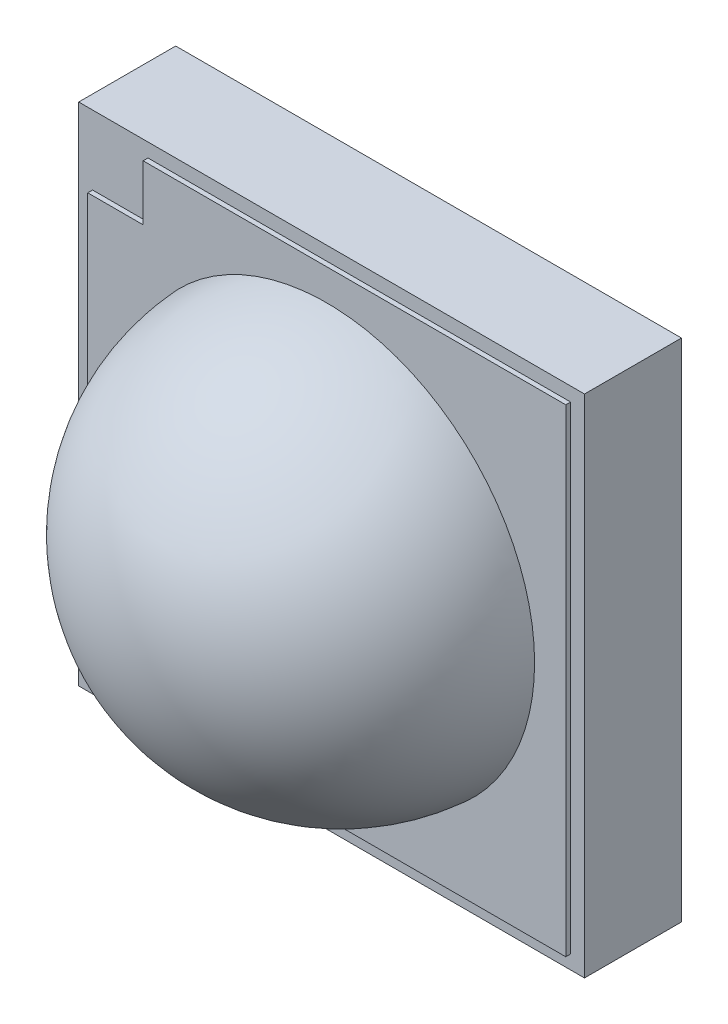
SolidWorks part; units mm, degrees
ref_plane "Front" through (0, 0, 0) normal (0, 0, 1) x (1, 0, 0)
ref_plane "Top" through (0, 0, 0) normal (0, 1, 0) x (1, 0, 0)
ref_plane "Right" through (0, 0, 0) normal (1, 0, 0) x (0, 0, -1)
sketch "Эскиз1" plane through (0, 0, 0) normal (0, 0, 1) x (1, 0, 0)
  line L1 (0.725, -1.625) -> (-0.525, -1.625)
  line L2 (0.725, -1.625) -> (0.725, 1.625)
  line L3 (0.725, 1.625) -> (-0.725, 1.625)
  line L4 (-0.725, -1.425) -> (-0.725, 1.625)
  line L5 (0.725, -1.625) -> (-0.725, 1.625) construction
  line L6 (0.725, 1.625) -> (-0.725, -1.625) construction
  line L7 (1.635, -1.625) -> (1.105, -1.625)
  line L8 (-1.105, -1.625) -> (-1.635, -1.625)
  line L9 (-1.105, -1.625) -> (-1.105, -0.875)
  line L10 (-1.105, -0.875) -> (-1.635, -0.875)
  line L11 (-1.635, -1.625) -> (-1.635, -0.875)
  line L12 (-1.105, -1.625) -> (-1.635, -0.875) construction
  line L13 (-1.105, -0.875) -> (-1.635, -1.625) construction
  line L14 (1.635, -1.625) -> (1.635, -0.875)
  line L15 (1.635, -0.875) -> (1.105, -0.875)
  line L16 (1.105, -1.625) -> (1.105, -0.875)
  line L17 (1.635, -0.375) -> (1.105, -0.375)
  line L18 (1.635, -0.375) -> (1.635, 0.375)
  line L19 (1.635, 0.375) -> (1.105, 0.375)
  line L20 (1.105, -0.375) -> (1.105, 0.375)
  line L21 (1.635, 0.875) -> (1.105, 0.875)
  line L22 (1.635, 0.875) -> (1.635, 1.625)
  line L23 (1.635, 1.625) -> (1.105, 1.625)
  line L24 (1.105, 0.875) -> (1.105, 1.625)
  line L25 (-1.105, -0.375) -> (-1.635, -0.375)
  line L26 (-1.105, -0.375) -> (-1.105, 0.375)
  line L27 (-1.105, 0.375) -> (-1.635, 0.375)
  line L28 (-1.635, -0.375) -> (-1.635, 0.375)
  line L29 (-1.105, 0.875) -> (-1.635, 0.875)
  line L30 (-1.105, 0.875) -> (-1.105, 1.625)
  line L31 (-1.105, 1.625) -> (-1.635, 1.625)
  line L32 (-1.635, 0.875) -> (-1.635, 1.625)
  line L34 (-0.525, -1.625) -> (-0.725, -1.425)
  point P0 (0, 0)
  point P8 (-1.37, -1.25)
  dimension "D1" = 1.45
  dimension "D2" = 3.25
  dimension "D4" = 0.53
  dimension "D5" = 0.75
  dimension "D6" = 0.38
  dimension "D9" = 3.27
  dimension "D10" = 0.5
  dimension "D7" = 2
  dimension "D8" = 3
extrude "Бобышка-Вытянуть1" add sketch "Эскиз1" along normal blind 0.035
sketch "Эскиз2" plane through (0, 0, 0.035) normal (0, 0, 1) x (1, 0, 0)
  line L1 (-1.825, -1.825) -> (1.825, -1.825)
  line L2 (-1.825, -1.825) -> (-1.825, 1.825)
  line L3 (-1.825, 1.825) -> (1.825, 1.825)
  line L4 (1.825, -1.825) -> (1.825, 1.825)
  line L5 (-1.825, -1.825) -> (1.825, 1.825) construction
  line L6 (-1.825, 1.825) -> (1.825, -1.825) construction
  point P0 (0, 0)
  dimension "D1" = 3.65
extrude "Бобышка-Вытянуть2" add sketch "Эскиз2" along normal blind 0.7
sketch "Эскиз4" plane through (0, 0, 0.735) normal (0, 0, 1) x (1, 0, 0)
  line L0 (1.725, 1.725) -> (1.725, -1.725)
  line L5 (-1.725, -1.725) -> (1.725, 1.725) construction
  line L6 (-1.725, 1.725) -> (1.725, -1.725) construction
  line L9 (1.725, -1.725) -> (-1.725, -1.725)
  line L10 (1.725, 1.725) -> (-1.325, 1.725)
  line L11 (-1.325, 1.725) -> (-1.325, 1.325)
  line L12 (-1.325, 1.325) -> (-1.725, 1.325)
  line L13 (-1.725, 1.325) -> (-1.725, -1.725)
  line L14 (-1.725, 1.325) -> (-1.725, 1.725) construction
  line L15 (-1.725, 1.725) -> (-1.325, 1.725) construction
  point P0 (0, 0)
  dimension "D1" = 3.45
  dimension "D2" = 0.4
extrude "Бобышка-Вытянуть3" add sketch "Эскиз4" along normal blind 0.035
sketch "Эскиз3" plane through (0, 0, 0) normal (0, 1, 0) x (1, 0, 0)
  line L0 (0, -0.77) -> (0, -2.17)
  line L1 (0, -0.77) -> (-1.5, -0.77)
  line L3 (1.725, -0.77) -> (-1.325, -0.77) construction
  arc A0 (-1.5, -0.77) -> (0, -2.17) centre (0, -0.6664) ccw
  dimension "D1" = 1.4
  dimension "D2" = 1.5
revolve "Повернуть1" add sketch "Эскиз3" angle 360 about L0
